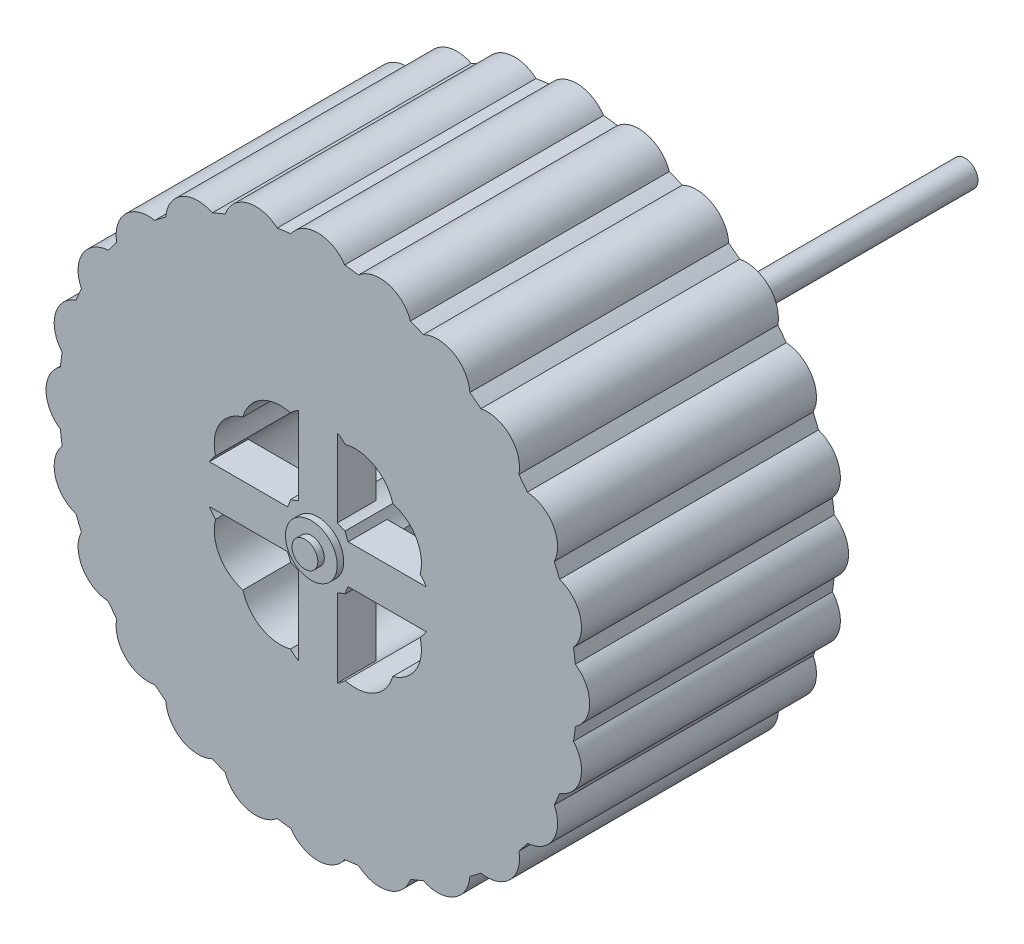
SolidWorks part; units mm, degrees
ref_plane "Front Plane" through (0, 0, 0) normal (0, 0, 1) x (1, 0, 0)
ref_plane "Top Plane" through (0, 0, 0) normal (0, 1, 0) x (1, 0, 0)
ref_plane "Right Plane" through (0, 0, 0) normal (1, 0, 0) x (0, 0, -1)
sketch "Sketch1" plane through (0, 0, 0) normal (0, 0, 1) x (1, 0, 0)
  circle A0 centre (0, 0) radius 50.8
extrude "Boss-Extrude3" add sketch "Sketch1" along normal blind 50.8 contours A0
sketch "Sketch5" plane through (0, 0, 50.8) normal (0, 0, 1) x (1, 0, 0)
  circle A0 centre (0, 14.6768) radius 7.62
  circle A1 centre (7.3384, 12.7105) radius 7.62
  circle A2 centre (12.7105, 7.3384) radius 7.62
  circle A3 centre (14.6768, 0) radius 7.62
  circle A4 centre (12.7105, -7.3384) radius 7.62
  circle A5 centre (7.3384, -12.7105) radius 7.62
  circle A6 centre (0, -14.6768) radius 7.62
  circle A7 centre (-7.3384, -12.7105) radius 7.62
  circle A8 centre (-12.7105, -7.3384) radius 7.62
  circle A9 centre (-14.6768, 0) radius 7.62
  circle A10 centre (-12.7105, 7.3384) radius 7.62
  circle A11 centre (-7.3384, 12.7105) radius 7.62
  point P27 (0, 0)
  dimension "D1" = 12
extrude "Cut-Extrude2" cut sketch "Sketch5" against normal blind 50.8 contours A0 | A1 | A2 | A3 | A4 | A5 | A6 | A7 | A8 | A9 | A10 | A11
sketch "Sketch6" plane through (0, 0, 50.8) normal (0, 0, 1) x (1, 0, 0)
  line L1 (50.6569, 3.81) -> (-50.6569, 3.81)
  line L2 (50.6569, 3.81) -> (50.6569, -3.81)
  line L3 (50.6569, -3.81) -> (-50.6569, -3.81)
  line L4 (-50.6569, 3.81) -> (-50.6569, -3.81)
  line L5 (50.6569, 3.81) -> (-50.6569, -3.81) construction
  line L6 (50.6569, -3.81) -> (-50.6569, 3.81) construction
  line L7 (-3.81, 50.6569) -> (3.81, 50.6569)
  line L8 (-3.81, 50.6569) -> (-3.81, -50.6569)
  line L9 (-3.81, -50.6569) -> (3.81, -50.6569)
  line L10 (3.81, 50.6569) -> (3.81, -50.6569)
  line L11 (-3.81, 50.6569) -> (3.81, -50.6569) construction
  line L12 (-3.81, -50.6569) -> (3.81, 50.6569) construction
  circle A0 centre (0, 0) radius 50.8 construction
  point P0 (0, 0)
  point P8 (0, 0)
  dimension "D1" = 7.62
extrude "Boss-Extrude4" add sketch "Sketch6" against normal blind 7.62 contours L10 L9 L8 L7 | L1 L4 L3 L2
sketch "Sketch7" plane through (0, 0, 50.8) normal (0, 0, 1) x (1, 0, 0)
  circle A0 centre (0, 0) radius 5.08
extrude "Boss-Extrude5" add sketch "Sketch7" along normal blind 1.27
sketch "Sketch8" plane through (0, 0, 52.07) normal (0, 0, 1) x (1, 0, 0)
  circle A0 centre (0, 0) radius 2.54
extrude "Boss-Extrude6" add sketch "Sketch8" along normal blind 1.27
sketch "Sketch9" plane through (0, 0, 0) normal (0, 0, -1) x (-1, 0, 0)
  circle A0 centre (0, 0) radius 2.54
extrude "Boss-Extrude7" add sketch "Sketch9" along normal blind 76.2
sketch "Sketch10" plane through (0, 0, 50.8) normal (0, 0, 1) x (1, 0, 0)
  circle A0 centre (0, 46.99) radius 6.35
  circle A4 centre (12.1619, 45.3889) radius 6.35
  circle A5 centre (23.495, 40.6945) radius 6.35
  circle A6 centre (33.2269, 33.2269) radius 6.35
  circle A7 centre (40.6945, 23.495) radius 6.35
  circle A8 centre (45.3889, 12.1619) radius 6.35
  circle A9 centre (46.99, 0) radius 6.35
  circle A10 centre (45.3889, -12.1619) radius 6.35
  circle A11 centre (40.6945, -23.495) radius 6.35
  circle A12 centre (33.2269, -33.2269) radius 6.35
  circle A13 centre (23.495, -40.6945) radius 6.35
  circle A14 centre (12.1619, -45.3889) radius 6.35
  circle A15 centre (0, -46.99) radius 6.35
  circle A16 centre (-12.1619, -45.3889) radius 6.35
  circle A17 centre (-23.495, -40.6945) radius 6.35
  circle A18 centre (-33.2269, -33.2269) radius 6.35
  circle A19 centre (-40.6945, -23.495) radius 6.35
  circle A20 centre (-45.3889, -12.1619) radius 6.35
  circle A21 centre (-46.99, 0) radius 6.35
  circle A22 centre (-45.3889, 12.1619) radius 6.35
  circle A23 centre (-40.6945, 23.495) radius 6.35
  circle A24 centre (-33.2269, 33.2269) radius 6.35
  circle A25 centre (-23.495, 40.6945) radius 6.35
  circle A26 centre (-12.1619, 45.3889) radius 6.35
  point P54 (0, 0)
  circle M34 centre (0, 0) radius 50.8
  dimension "D1" = 46.99
  dimension "D2" = 24
extrude "Boss-Extrude8" add sketch "Sketch10" against normal blind 50.8 contours A11 M34 | A26 | A25 | A24 | A23 | A22 | A21 | A20 | A19 | A18 | A17 | A16 | A15 | A14 | A13 | A12 | A10 | A9 | A8 | A7 | A6 | A5 | A4 | A0
sketch "Sketch11" plane through (0, 0, 0) normal (0, 0, -1) x (-1, 0, 0)
  line L1 (3.81, 52.07) -> (-3.81, 52.07)
  line L2 (3.81, 52.07) -> (3.81, -52.07)
  line L3 (3.81, -52.07) -> (-3.81, -52.07)
  line L4 (-3.81, 52.07) -> (-3.81, -52.07)
  line L5 (3.81, 52.07) -> (-3.81, -52.07) construction
  line L6 (3.81, -52.07) -> (-3.81, 52.07) construction
  line L7 (52.07, 3.81) -> (-52.07, 3.81)
  line L8 (52.07, 3.81) -> (52.07, -3.81)
  line L9 (52.07, -3.81) -> (-52.07, -3.81)
  line L10 (-52.07, 3.81) -> (-52.07, -3.81)
  line L11 (52.07, 3.81) -> (-52.07, -3.81) construction
  line L12 (52.07, -3.81) -> (-52.07, 3.81) construction
  arc A0 (-5.2748, -50.5254) -> (5.2748, -50.5254) centre (0, -46.99) ccw construction
  arc A1 (-50.5254, 5.2748) -> (-50.5254, -5.2748) centre (-46.99, 0) ccw construction
  point P0 (0, 0)
  point P9 (0, 0)
  point P17 (-52.07, 0)
  dimension "D1" = 7.62
extrude "Boss-Extrude9" add sketch "Sketch11" against normal blind 7.62 contours L7 L10 L9 L8 | L4 L3 L2 L1
sketch "Sketch12" plane through (0, 0, 0) normal (0, 0, -1) x (-1, 0, 0)
  circle A0 centre (0, 0) radius 6.35
extrude "Boss-Extrude10" add sketch "Sketch12" along normal blind 1.27
